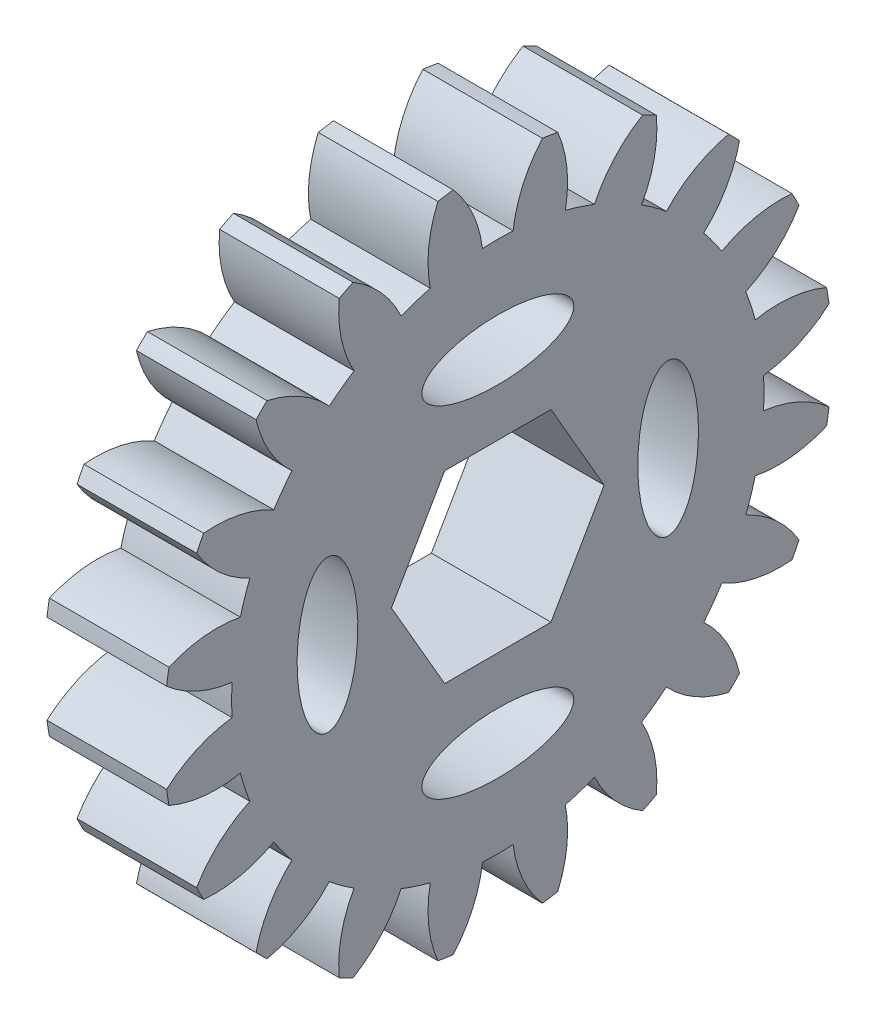
SolidWorks part; units mm, degrees
ref_plane "Plane1" through (0, 0, 0) normal (0, 0, 1) x (1, 0, 0)
ref_plane "Plane2" through (0, 0, 0) normal (0, 1, 0) x (1, 0, 0)
ref_plane "Plane3" through (0, 0, 0) normal (1, 0, 0) x (0, 0, -1)
sketch "HoldingSke" plane through (0, 0, 0) normal (0, 1, 0) x (1, 0, 0)
  line L0 (0, 0) -> (477.3639, -173.7462)
  line L1 (-15, 0) -> (100, 0) construction
  line L2 (0, 0) -> (-2.1039, 2.3779)
  line L3 (0, 0) -> (-11.863, 4.5341)
  line L4 (0, 0) -> (8.1152, 2.9537)
  line L5 (0, 0) -> (-47.5972, -17.7524)
  line L6 (0, 0) -> (-4.1448, -2.7965)
  line L7 (-2.1039, 2.3779) -> (8.8308, 51.9871)
  line L8 (-76.2, 54.61) -> (-75.184, 54.61)
  line L9 (-71.009, 38.7566) -> (-53.1078, 45.2721)
  line L10 (-76.2, 71.12) -> (104.1128, 71.12)
  line L11 (0, 0) -> (-5, 0)
  line L12 (-76.2, 101.6) -> (-76.1492, 101.6)
  line L13 (24.9733, 27.94) -> (52.9518, 28.4284)
  line L14 (24.9733, 27.94) -> (25.0241, 27.9398)
  line L15 (24.9733, 27.94) -> (100.4021, 29.52)
  circle A0 centre (0, 0) radius 0.3969
  circle A1 centre (0, 0) radius 11.1252
  circle A2 centre (0, 0) radius 38.1
  circle A3 centre (0, 0) radius 0.3969
  dimension "MHD" = 22.2504
  dimension "Hub_dia" = 76.2
  dimension "Bore" = 0.7937
  dimension "MBD" = 0.7937
  dimension "Num_teeth" = 20
  dimension "Pitch" = 508
  dimension "Overall_len" = 50.8
  dimension "Show_teeth" = 20
  dimension "Thickness" = 5
  dimension "OAL" = 50.8001
  dimension "T_dim" = 1.016
  dimension "Ap" = 20
  dimension "H" = 19.05
  dimension "Pitch_radius" = 180.3128
  dimension "Width" = 5
  dimension "Backlash" = 0.0508
  dimension "Addendum_fac" = 1
  dimension "Dedendum_fac" = 1.2
  dimension "Clearance_fac" = 0.2
  dimension "Dedendum_add" = 0.0508
sketch "BasProSke" plane through (0, 0, 0) normal (0, 1, 0) x (1, 0, 0)
  line L0 (-10, 0) -> (60, 0) construction
  line L1 (0, 0) -> (0, 13.97)
  line L2 (0, 0) -> (5, 0)
  line L3 (5, 0) -> (5, 13.97)
  line L4 (5, 13.97) -> (0, 13.97)
  dimension "Thickness" = 5
  dimension "Diameter" = 27.94
revolve "Base-Revolve" add sketch "BasProSke" angle 360 about L0
sketch "TooCutSke" plane through (0, 0, 0) normal (1, 0, 0) x (0, 0, -1)
  line L1 (0, 0) -> (0, 107) construction
  line L2 (0, 0) -> (-1.0853, 12.6535) construction
  line L3 (0, 0) -> (-3.9633, 25.0231) construction
  line L4 (-1.0853, 12.6535) -> (-1.9816, 12.5116) construction
  arc A0 (0.6405, 11.1067) -> (-0.6405, 11.1067) centre (0, 0) ccw
  arc A1 (1.8856, 13.8678) -> (-1.8856, 13.8678) centre (0, 0) ccw
  circle A2 centre (0, 0) radius 12.7 construction
  circle A3 centre (0, 0) radius 11.9341 construction
  arc A4 (-0.6405, 11.1067) -> (-1.8856, 13.8678) centre (-5.6834, 10.4939) ccw
  arc A5 (1.8856, 13.8678) -> (0.6405, 11.1067) centre (5.6834, 10.4939) ccw
  dimension "Root_dia" = 22.2504
  dimension "Overcut_dia" = 27.9908
  dimension "Pitch_dia" = 25.4
  dimension "Base_dia" = 23.8682
  dimension "Flank_rad" = 5.08
  dimension "Half_ang" = 9
  dimension "Half_CT" = 0.9075
extrude "ToothCut" cut sketch "TooCutSke" along normal through all
fillet "Breaks" [suppressed] radius 0.0254
fillet "RootFillets" [suppressed] radius 0.3048
pattern_circular "TeethCuts" count 20 every 18 about axis through (-10, 0, 0) along (1, 0, 0) of "ToothCut", "RootFillets", "Breaks"
sketch "HubNeaOneSke" plane through (0, 0, 0) normal (-1, 0, 0) x (0, 0, 1)
  circle A0 centre (0, 0) radius 11.1252
  dimension "Diameter" = 22.2504
extrude "HubNearOne" [suppressed] add sketch "HubNeaOneSke" along normal blind 45.8001
sketch "HubNeaBotSke" plane through (0, 0, 0) normal (-1, 0, 0) x (0, 0, 1)
  circle A0 centre (0, 0) radius 11.1252
  dimension "Diameter" = 22.2504
extrude "HubNearBoth" [suppressed] add sketch "HubNeaBotSke" along normal blind 22.9
ref_plane "FarPln" through (5, 0, 0) normal (1, 0, 0) x (0, 0, -1)
sketch "HubFarSke" plane through (5, 0, 0) normal (1, 0, 0) x (0, 0, -1)
  circle A0 centre (0, 0) radius 11.1252
  dimension "Diameter" = 22.2504
extrude "HubFar" [suppressed] add sketch "HubFarSke" along normal blind 22.9
sketch "BorSke" plane through (0, 0, 0) normal (1, 0, 0) x (0, 0, -1)
  circle A0 centre (0, 0) radius 0.3969
  dimension "Diameter" = 0.7937
extrude "Bore" cut sketch "BorSke" along normal mid plane 101.6001
sketch "KeySke" plane through (0, 0, 0) normal (1, 0, 0) x (0, 0, -1)
  line L0 (-0.127, 0) -> (-0.127, 0.6191)
  line L1 (-0.127, 0.6191) -> (0.127, 0.6191)
  line L2 (0.127, 0.6191) -> (0.127, 0)
  line L3 (0, 0) -> (0, 34) construction
  line L4 (-0.127, 0) -> (0.127, 0)
  dimension "Offset" = 0.6191
  dimension "Width" = 0.254
extrude "Keyway" [suppressed] cut sketch "KeySke" along normal mid plane 101.6001
pattern_circular "Keyway2" [suppressed] count 2 every 90 about axis through (-10, 0, 0) along (1, 0, 0)
sketch "Sketch1" plane through (5, 0, 0) normal (1, 0, 0) x (0, 0, -1)
  line L1 (2.2225, 3.8495) -> (-2.2225, 3.8495)
  line L2 (-2.2225, 3.8495) -> (-4.445, 0)
  line L3 (-4.445, 0) -> (-2.2225, -3.8495)
  line L4 (-2.2225, -3.8495) -> (2.2225, -3.8495)
  line L5 (2.2225, -3.8495) -> (4.445, 0)
  line L6 (4.445, 0) -> (2.2225, 3.8495)
  circle A0 centre (0, 0) radius 3.8495 construction
  dimension "D1" = 8.89
extrude "Cut-Extrude1" cut sketch "Sketch1" against normal through all
sketch "Sketch2" plane through (5, 0, 0) normal (1, 0, 0) x (0, 0, -1)
  line L2 (2.2225, 3.8495) -> (-2.2225, 3.8495) construction
  ellipse E0 centre (0, 7.1195) end of major axis (-3.175, 7.1195) minor radius 1.27
  point P8 (0, 0)
  point P9 (0, 0)
  dimension "D1" = 2
  dimension "D2" = 2.54
extrude "Cut-Extrude2" cut sketch "Sketch2" against normal through all
pattern_circular "CirPattern1" count 4 over 360 about axis through (5, 0, 0) along (-1, 0, 0) of "Cut-Extrude2"
equation "' \"Pitch@HoldingSke\" = 4"
equation "' \"Num_teeth@HoldingSke\" = 12"
equation "' \"Ap@HoldingSke\" =  20"
equation "' \"Ap@HoldingSke\" = 20"
equation "' \"Width@HoldingSke\" = 0.5"
equation "' \"Hub_dia@HoldingSke\"= 1"
equation "' \"Hub_dia@HoldingSke\" = 1"
equation "' \"Overall_len@HoldingSke\" = 1.0"
equation "' \"Bore@HoldingSke\" = 0.75"
equation "' \"T_dim@HoldingSke\" = 0.85"
equation "' \"Width@KeySke\" = 0.25"
equation "' \"Show_teeth@HoldingSke\" = 13"
equation "' \"Backlash@HoldingSke\" = 0.009"
equation "' \"Addendum_fac@HoldingSke\" = 1.0"
equation "' \"Dedendum_fac@HoldingSke\" = 1.25"
equation "' \"Dedendum_add@HoldingSke\" = 0.00005"
equation "' \"Clearance_fac@HoldingSke\" = 0.25"
equation "' \"Pitch@HoldingSke\" = 0.5"
equation "' \"Num_teeth@HoldingSke\" = 23"
equation "' \"Show_teeth@HoldingSke\" = 23"
equation "' \"Backlash@HoldingSke\" = 0.0375"
equation "\"Overcut_dia@TooCutSke\" = (\"Num_teeth@HoldingSke\" + 2 * \"Addendum_fac@HoldingSke\") / \"Pitch@HoldingSke\" + 0.002"
equation "\"Pitch_dia@TooCutSke\" = \"Num_teeth@HoldingSke\" / \"Pitch@HoldingSke\""
equation "\"Base_dia@TooCutSke\" = \"Num_teeth@HoldingSke\" / \"Pitch@HoldingSke\" * cos((\"Ap@HoldingSke\"  * 3.14159265 / 180))"
equation "\"Root_dia@TooCutSke\" = (\"Num_teeth@HoldingSke\" + 2) / \"Pitch@HoldingSke\" - 2 * (\"Addendum_fac@HoldingSke\" + \"Dedendum_fac@HoldingSke\") / \"Pitch@HoldingSke\" - \"Dedendum_add@HoldingSke\" * 2"
equation "\"Half_ang@TooCutSke\" = 180 / \"Num_teeth@HoldingSke\""
equation "\"Half_CT@TooCutSke\" = \"Num_teeth@HoldingSke\" / \"Pitch@HoldingSke\" * sin((3.14159265 / 2 / \"Num_teeth@HoldingSke\")) / 2 - 7 * \"Backlash@HoldingSke\" / 4"
equation "\"Flank_rad@TooCutSke\" = \"Num_teeth@HoldingSke\" / \"Pitch@HoldingSke\" / 5"
equation "\"Radius@RootFillets\" = \"Clearance_fac@HoldingSke\" / \"Pitch@HoldingSke\" + \"Dedendum_add@HoldingSke\""
equation "\"Break_rad@Breaks\" = 0.02 / \"Pitch@HoldingSke\""
equation "\"Thickness@HoldingSke\" = \"Width@HoldingSke\""
equation "\"OAL@HoldingSke\" = \"Thickness@HoldingSke\""
equation "\"MHD@HoldingSke\" = (\"Num_teeth@HoldingSke\" + 2) / \"Pitch@HoldingSke\" - 2 * (\"Addendum_fac@HoldingSke\" + \"Dedendum_fac@HoldingSke\")  / \"Pitch@HoldingSke\" - \"Dedendum_add@HoldingSke\" * 2"
equation "\"MBD@HoldingSke\" = (\"Num_teeth@HoldingSke\" + 2) / \"Pitch@HoldingSke\" - 2 * (\"Addendum_fac@HoldingSke\" + \"Dedendum_fac@HoldingSke\")  / \"Pitch@HoldingSke\" - \"Dedendum_add@HoldingSke\" * 2 - 0.002"
equation "\"MHD@HoldingSke\" = ((sgn( \"MHD@HoldingSke\" - \"Hub_dia@HoldingSke\" )-1)*( \"MHD@HoldingSke\" - \"Hub_dia@HoldingSke\" ))/-2+ \"Hub_dia@HoldingSke\""
equation "\"MBD@HoldingSke\" = ((sgn( \"MBD@HoldingSke\" - \"Bore@HoldingSke\" )-1)*( \"MBD@HoldingSke\" - \"Bore@HoldingSke\" ))/-2+ \"Bore@HoldingSke\""
equation "\"OAL@HoldingSke\" = ((sgn( \"OAL@HoldingSke\" - \"Overall_len@HoldingSke\" )+1)*( \"OAL@HoldingSke\" - \"Overall_len@HoldingSke\" ))/2 + \"Overall_len@HoldingSke\" + 0.000002"
equation "\"Num_teeth@TeethCuts\" = int( \"Show_teeth@HoldingSke\" ) + 1"
equation "\"Num_teeth@TeethCuts\" = ((sgn( \"Num_teeth@TeethCuts\" - \"Num_teeth@HoldingSke\" )-1)*( \"Num_teeth@TeethCuts\" - \"Num_teeth@HoldingSke\" ))/-2+ \"Num_teeth@HoldingSke\""
equation "\"Num_teeth@TeethCuts\" = ((sgn( \"Num_teeth@TeethCuts\" - 2.0)+1)*( \"Num_teeth@TeethCuts\" - 2.0))/2 +2.0"
equation "\"Angle@TeethCuts\" = 360.0 / \"Num_teeth@HoldingSke\""
equation "\"Diameter@BasProSke\" = (\"Num_teeth@HoldingSke\" + 2 * \"Addendum_fac@HoldingSke\") / \"Pitch@HoldingSke\""
equation "\"Thickness@BasProSke\"  = \"Thickness@HoldingSke\""
equation "' \"Fillet_rad@BasProSke\" =  \"Thickness@HoldingSke\" * 0.05"
equation "' \"Fillet_rad@BasProSke\" = \"Thickness@HoldingSke\" * 0.05"
equation "\"MHD@HoldingSke\" = ((sgn( \"MHD@HoldingSke\" - \"Root_dia@TooCutSke\" )-1)*( \"MHD@HoldingSke\" - \"Root_dia@TooCutSke\" ))/-2+ \"Root_dia@TooCutSke\""
equation "\"Diameter@HubNeaOneSke\" = \"MHD@HoldingSke\""
equation "\"Length@HubNearOne\" = \"OAL@HoldingSke\" - \"Thickness@BasProSke\""
equation "\"Diameter@HubNeaBotSke\" = \"MHD@HoldingSke\""
equation "\"Length@HubNearBoth\" = ( \"OAL@HoldingSke\" - \"Thickness@BasProSke\" ) / 2.0"
equation "\"Thickness@FarPln\" = \"Thickness@BasProSke\""
equation "\"Diameter@HubFarSke\" = \"MHD@HoldingSke\""
equation "\"Length@HubFar\" = ( \"OAL@HoldingSke\" - \"Thickness@BasProSke\" ) / 2.0"
equation "\"Diameter@BorSke\" = \"MBD@HoldingSke\""
equation "\"D1@Bore\" = \"OAL@HoldingSke\" * 2.0"
equation "\"D1@Keyway\" = \"OAL@HoldingSke\" * 2.0"
equation "\"Offset@KeySke\" = \"T_dim@HoldingSke\" - \"MBD@HoldingSke\" / 2.0"
